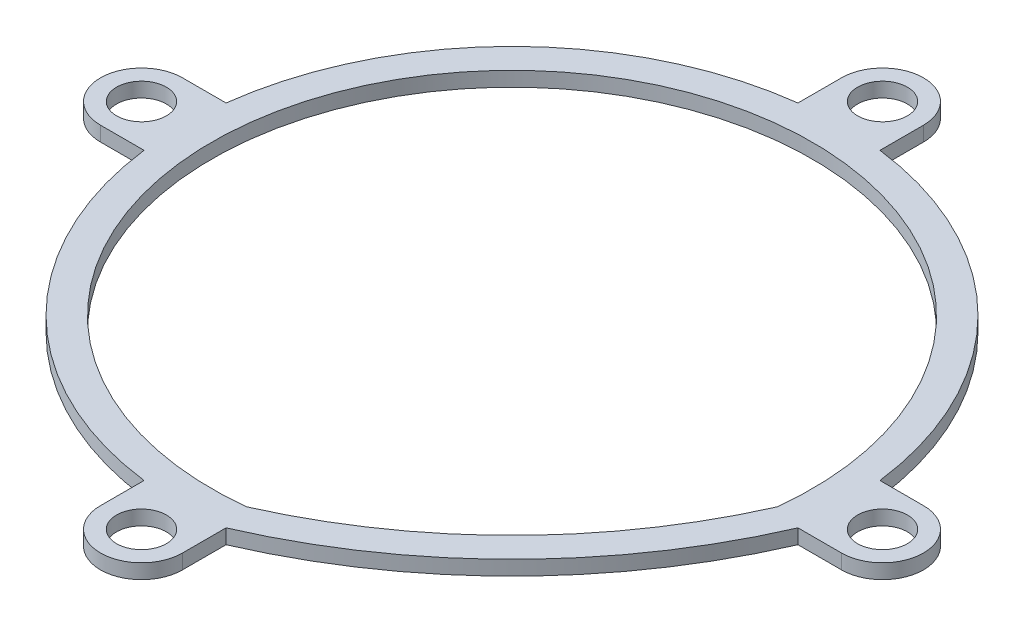
SolidWorks part; units mm, degrees
ref_plane "Спереди" through (0, 0, 0) normal (0, 0, 1) x (1, 0, 0)
ref_plane "Сверху" through (0, 0, 0) normal (0, 1, 0) x (1, 0, 0)
ref_plane "Справа" through (0, 0, 0) normal (1, 0, 0) x (0, 0, -1)
sketch "Эскиз1" plane through (0, 0, 0) normal (0, 1, 0) x (1, 0, 0)
  line L0 (22.3251, -2.8) -> (25.3, -2.8)
  line L1 (25.3, 2.8) -> (22.3251, 2.8)
  line L2 (2.8, 22.3251) -> (2.8, 25.3)
  line L3 (-2.8, 25.3) -> (-2.8, 22.3251)
  line L4 (-22.3251, 2.8) -> (-25.3, 2.8)
  line L5 (-25.3, -2.8) -> (-22.3251, -2.8)
  line L6 (-2.8, -22.3251) -> (-2.8, -25.3)
  line L7 (2.8, -25.3) -> (2.8, -22.3251)
  arc A0 (2.8, -22.3251) -> (22.3251, -2.8) centre (-12.1018, 12.1018) ccw
  arc A1 (25.3, -2.8) -> (25.3, 2.8) centre (25.3, 0) ccw
  arc A2 (22.3251, 2.8) -> (2.8, 22.3251) centre (0, 0) ccw
  arc A3 (2.8, 25.3) -> (-2.8, 25.3) centre (0, 25.3) ccw
  arc A4 (-2.8, 22.3251) -> (-22.3251, 2.8) centre (0, 0) ccw
  arc A5 (-25.3, 2.8) -> (-25.3, -2.8) centre (-25.3, 0) ccw
  arc A6 (-22.3251, -2.8) -> (-2.8, -22.3251) centre (0, 0) ccw
  arc A7 (-2.8, -25.3) -> (2.8, -25.3) centre (0, -25.3) ccw
  arc A8 (20.3739, -2.2699) -> (2.2699, -20.3739) centre (0, 0) ccw
  arc A9 (2.2699, -20.3739) -> (20.3739, -2.2699) centre (-12.1018, 12.1018) ccw
extrude "Бобышка-Вытянуть1" add sketch "Эскиз1" along normal blind 1
hole_wizard "Отверстие с зазором M31" positions "Эскиз2" profile "Эскиз3" hole size "M3" standard "ISO" end condition through all
sketch "Эскиз2" plane through (0, 1, 0) normal (0, 1, 0) x (1, 0, 0)
  point P0 (-25.3, 0)
  point P3 (0, 25.3)
  point P6 (25.3, 0)
  point P9 (0, -25.3)
sketch "Эскиз3" plane through (-25.3, 1, 0) normal (1, 0, 0) x (0, 0, 1)
  line L0 (0, 0) -> (0, 1)
  line L1 (0, 1) -> (1.7, 1)
  line L2 (1.7, 1) -> (1.7, 0)
  line L5 (1.7, 0) -> (0, 0)
  line L11 (0, -6.35) -> (0, 107.95) construction
  dimension "Диаметр сквозного отверстия" = 3.4
  dimension "Глубина сквозного отверстия" = 1
